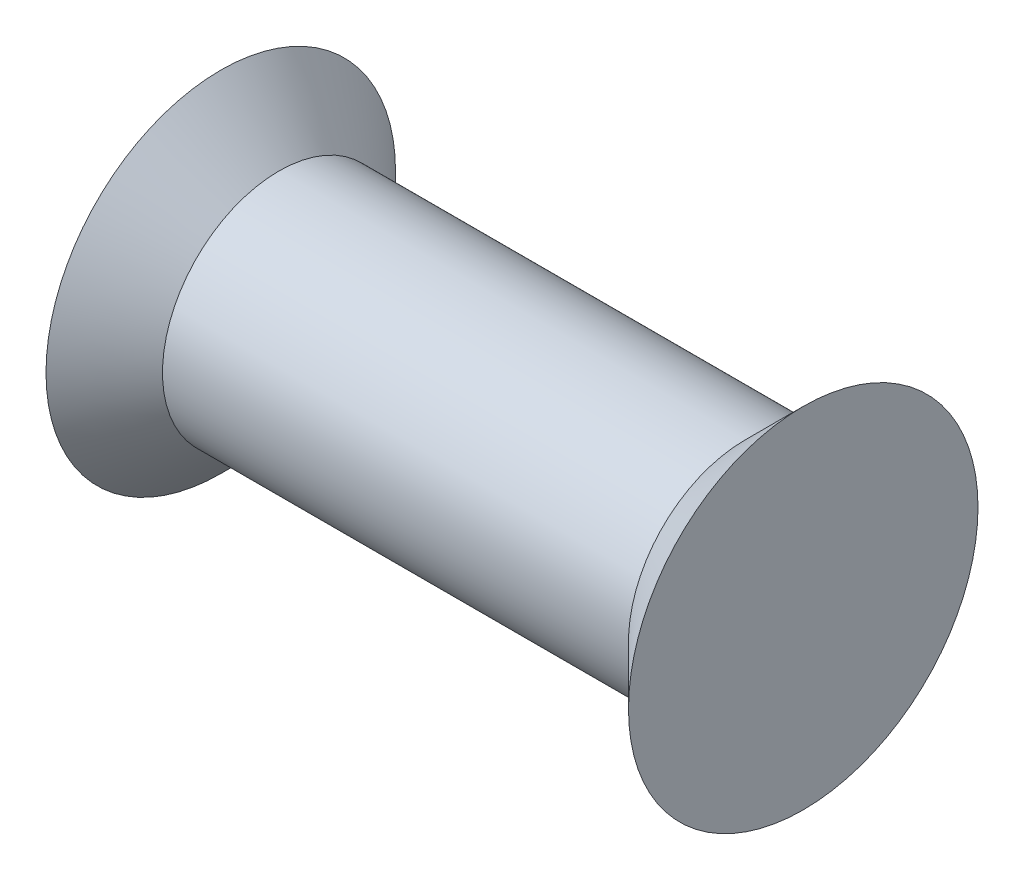
SolidWorks part; units mm, degrees
ref_plane "前视基准面" through (0, 0, 0) normal (0, 0, 1) x (1, 0, 0)
ref_plane "上视基准面" through (0, 0, 0) normal (0, 1, 0) x (1, 0, 0)
ref_plane "右视基准面" through (0, 0, 0) normal (1, 0, 0) x (0, 0, -1)
sketch "草图1" plane through (0, 0, 0) normal (0, 0, 1) x (1, 0, 0)
  line L0 (2, 1) -> (2.5, 1.5)
  line L1 (0, 0) -> (2, 0)
  line L2 (0, 0) -> (0, 1)
  line L3 (0, 1) -> (2, 1)
  line L4 (2, 0) -> (2, 1)
  line L5 (2.5, 1.5) -> (2.5, 0)
  line L6 (2.5, 0) -> (2, 0)
  dimension "D1" = 2.5
  dimension "D2" = 45
  dimension "D3" = 1
  dimension "0.5" = 0.5
revolve "旋转1" add sketch "草图1" angle 360 about L1
mirror "镜向1" about plane through (0, 0, 0) normal (-1, 0, 0) of "旋转1"
